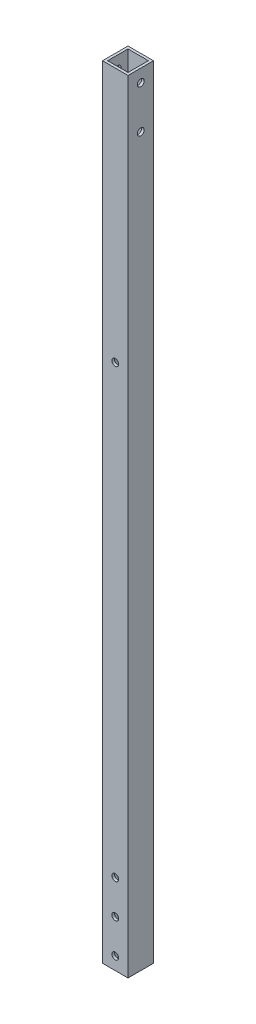
SolidWorks part; units mm, degrees
material "1060 合金"
ref_plane "正面" through (0, 0, 0) normal (0, 0, 1) x (1, 0, 0)
ref_plane "平面" through (0, 0, 0) normal (0, 1, 0) x (1, 0, 0)
ref_plane "右側面" through (0, 0, 0) normal (1, 0, 0) x (0, 0, -1)
sketch "ｽｹｯﾁ1" plane through (0, 0, 0) normal (0, 1, 0) x (1, 0, 0)
  line L1 (-7.5, -7.5) -> (7.5, -7.5)
  line L2 (-7.5, -7.5) -> (-7.5, 7.5)
  line L3 (-7.5, 7.5) -> (7.5, 7.5)
  line L4 (7.5, -7.5) -> (7.5, 7.5)
  line L5 (-7.5, -7.5) -> (7.5, 7.5) construction
  line L6 (-7.5, 7.5) -> (7.5, -7.5) construction
  point P0 (0, 0)
  dimension "D1" = 15
extrude "押し出し-薄板1" add sketch "ｽｹｯﾁ1" along normal blind 460 thin thin type one direction reverse wall 1.5
sketch "ｽｹｯﾁ2" plane through (7.5, 0, 0) normal (1, 0, 0) x (0, 0, -1)
  line L0 (0, 0) -> (0, 460) construction
  line L1 (-7.5, 460) -> (7.5, 460) construction
  circle A0 centre (0, 452.5) radius 2
  circle A1 centre (0, 427.5) radius 2
  dimension "D1" = 7.5
  dimension "D2" = 25
  dimension "D3" = 4
extrude "ｶｯﾄ - 押し出し1" cut sketch "ｽｹｯﾁ2" against normal through all
sketch "ｽｹｯﾁ3" plane through (0, 0, 7.5) normal (0, 0, 1) x (1, 0, 0)
  line L0 (0, 0) -> (0, 460) construction
  line L1 (-7.5, 460) -> (7.5, 460) construction
  line L2 (-7.5, 0) -> (7.5, 0) construction
  circle A0 centre (0, 7.5) radius 2
  circle A1 centre (0, 47.5) radius 2
  circle A2 centre (0, 27.5) radius 2
  circle A3 centre (0, 310) radius 2
  dimension "D1" = 7.5
  dimension "D2" = 40
  dimension "D3" = 4
  dimension "D4" = 20
  dimension "D5" = 150
  dimension "D6" = 4
extrude "ｶｯﾄ - 押し出し2" cut sketch "ｽｹｯﾁ3" against normal through all
